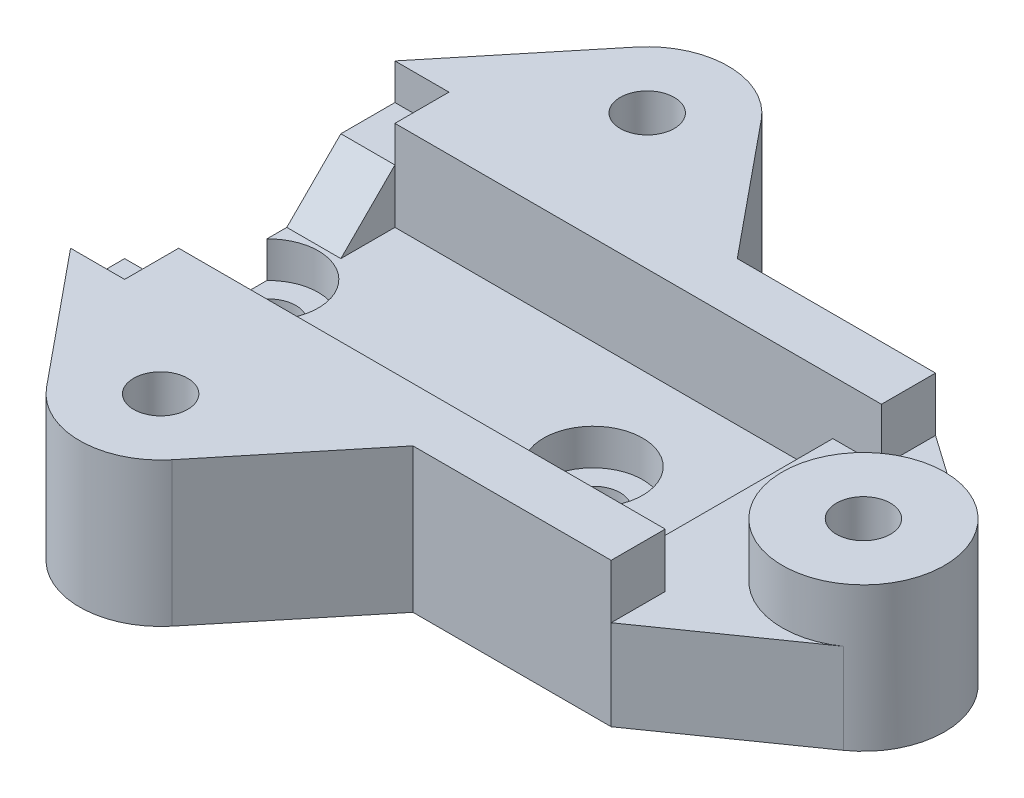
SolidWorks part; units mm, degrees
ref_plane "Front" through (0, 0, 0) normal (0, 0, 1) x (1, 0, 0)
ref_plane "Top" through (0, 0, 0) normal (0, 1, 0) x (1, 0, 0)
ref_plane "Right" through (0, 0, 0) normal (1, 0, 0) x (0, 0, -1)
sketch "Эскиз1" plane through (0, 0, 0) normal (0, 1, 0) x (1, 0, 0)
  line L0 (-9.0756, 0) -> (11.0252, 0) construction
  line L1 (0, 7.5126) -> (0, -7.9496) construction
  line L3 (15, 9) -> (-15, 9)
  line L4 (15, 9) -> (15, -9)
  line L5 (15, -9) -> (-15, -9)
  line L6 (-15, 9) -> (-15, -9)
  line L7 (15, 9) -> (-15, -9) construction
  line L8 (15, -9) -> (-15, 9) construction
  point P5 (0, 0)
  dimension "D1" = 18
  dimension "D2" = 30
extrude "Бобышка-Вытянуть1" add sketch "Эскиз1" along normal blind 3
sketch "Эскиз2" plane through (0, 3, 0) normal (0, 1, 0) x (1, 0, 0)
  line L0 (-15, 0) -> (15, 0) construction
  line L1 (-15, 9) -> (-15, -9) construction
  line L2 (15, -9) -> (15, 9) construction
  line L3 (-15, -9) -> (15, -9) construction
  line L4 (-12, -9) -> (15, -9)
  line L5 (-12, -9) -> (-12, -6)
  line L6 (-12, -6) -> (15, -6)
  line L7 (15, -9) -> (15, -6)
  line L8 (15, 9) -> (15, 6)
  line L9 (-12, 9) -> (-12, 6)
  line L10 (-12, 6) -> (15, 6)
  line L11 (-12, 9) -> (15, 9)
  dimension "D1" = 3
  dimension "D2" = 12
extrude "Бобышка-Вытянуть2" add sketch "Эскиз2" along normal blind 5
sketch "Эскиз3" plane through (0, 3, 0) normal (0, 1, 0) x (1, 0, 0)
  line L0 (15, -6) -> (-12, -6) construction
  line L1 (15, 6) -> (12.3, 6)
  line L2 (15, 6) -> (15, -6)
  line L3 (15, -6) -> (12.3, -6)
  line L4 (12.3, 6) -> (12.3, -6)
  line L8 (-12, 9) -> (-12, 6) construction
  dimension "D1" = 24.3
extrude "Бобышка-Вытянуть3" add sketch "Эскиз3" along normal blind 2
sketch "Эскиз4" plane through (0, 0, 0) normal (0, 1, 0) x (1, 0, 0)
  line L0 (15, -6) -> (15, 6) construction
  circle A0 centre (20, 0) radius 1.5
  circle A1 centre (20, 0) radius 4.5
  dimension "D1" = 3
  dimension "D3" = 9
  dimension "D2" = 5
extrude "Бобышка-Вытянуть4" add sketch "Эскиз4" along normal up to surface (8 mm away) separate body up to face at (1.5, 8, -7.5)
sketch "Эскиз5" plane through (0, 0, 0) normal (0, -1, 0) x (1, 0, 0)
  line L0 (15, 9) -> (22.5829, 3.6849)
  line L1 (15, -9) -> (22.5829, -3.6849)
  line L2 (15, 9) -> (15, -9)
  circle A0 centre (20, 0) radius 4.5 construction
  circle A2 centre (20, 0) radius 4.5
  arc A3 (22.5829, 3.6849) -> (22.5829, -3.6849) centre (20, 0) ccw
  dimension "D1" = 0
extrude "Бобышка-Вытянуть5" add sketch "Эскиз5" against normal up to surface (5 mm away) up to face at (13.65, 5, 0)
sketch "Эскиз7" plane through (-12, 0, 0) normal (-1, 0, 0) x (0, 0, 1)
  line L0 (9, 6) -> (6, 6)
  line L1 (9, 8) -> (9, 3) construction
  line L2 (6, 8) -> (6, 3) construction
  line L3 (6, 6) -> (3, 3)
  line L4 (3, 3) -> (9, 3)
  line L5 (9, 3) -> (9, 6)
  line L6 (0, 0) -> (0, 5.1893) construction
  line L7 (-3, 3) -> (-9, 3)
  line L8 (-9, 3) -> (-9, 6)
  line L9 (-9, 6) -> (-6, 6)
  line L10 (-6, 6) -> (-3, 3)
  dimension "D1" = 45
  dimension "D2" = 3
extrude "Бобышка-Вытянуть6" add sketch "Эскиз7" along normal up to surface (3 mm away) up to face at (-15, 1.5, 0)
sketch "Эскиз8" plane through (0, 0, 0) normal (0, 1, 0) x (1, 0, 0)
  line L0 (0, 0) -> (14.0942, 0) construction
  line L1 (-5.5, -13.5) -> (-5.5, 13.6667) construction
  line L2 (4, -9) -> (-2.0181, -16.3507)
  line L3 (-15, -9) -> (-8.9819, -16.3507)
  line L4 (-15, 9) -> (-8.9819, 16.3507)
  line L5 (4, 9) -> (-2.0181, 16.3507)
  line L6 (4, 9) -> (-15, 9)
  line L8 (4, -9) -> (-15, -9)
  line L10 (-15, -9) -> (15, -9) construction
  circle A0 centre (-5.5, 13.5) radius 1.5
  circle A1 centre (-5.5, -13.5) radius 1.5
  circle A2 centre (-5.5, 13.5) radius 4.5
  circle A3 centre (-5.5, -13.5) radius 4.5
  line M9 (-2.5606, -16.85) -> (-0.2025, -5.2975)
  line M13 (-0.2025, 5.2975) -> (-2.5606, 16.85)
  arc M14 (-2.5606, 16.85) -> (-8.4394, 16.85) centre (-5.5, 16.25) ccw
  line M15 (-8.4394, 16.85) -> (-10.7975, 5.2975)
  line M19 (-10.7975, -5.2975) -> (-8.4394, -16.85)
  arc M20 (-8.4394, -16.85) -> (-2.5606, -16.85) centre (-5.5, -16.25) ccw
  circle M26 centre (-5.5, -10.4167) radius 0.75
  circle M30 centre (-5.5, 10.4167) radius 0.75
  circle M32 centre (-5.5, -16.25) radius 0.75
  circle M33 centre (-5.5, 16.25) radius 0.75
  dimension "D3" = 9
  dimension "D4" = 3
  dimension "D2" = 9.5
  dimension "D5" = 13.5
sketch "Эскиз11" plane through (0, 0, 0) normal (0, -1, 0) x (1, 0, 0)
  line L0 (-15, -9) -> (-15, 9) construction
  circle A0 centre (-13, 0) radius 1.5
  point P0 (-15, 0)
  dimension "D1" = 3
  dimension "D2" = 2
extrude "Вырез-Вытянуть1" cut sketch "Эскиз11" against normal up to surface (3 mm away) up to face at (-5.1562, 3, 0)
sketch "Эскиз12" plane through (0, 3, 0) normal (0, 1, 0) x (1, 0, 0)
  circle A0 centre (-13, 0) radius 2.75
  dimension "D1" = 5.5
extrude "Вырез-Вытянуть2" cut sketch "Эскиз12" against normal blind 2
extrude "Бобышка-Вытянуть7" add sketch "Эскиз8" along normal up to surface (8 mm away) contours L5 A2 L6 M13 | A2 M14 M13 | A2 A0 M14 M15 M13 M30 M33 | A2 L6 M13 | A2 L4 L6 M15 | A2 M15 M14 | L6 A2 M15 | A3 L2 L8 M9 | A3 L8 M9 | A3 L8 M19 | A3 L8 L3 M19 | A3 A1 M20 M9 M19 M32 M26 | A3 M20 M9 | A3 M20 M19 | M26 | M32 | M33 | M30 up to face at (1.5, 8, 7.5)
sketch "Эскиз13" plane through (0, 0, 0) normal (0, -1, 0) x (1, 0, 0)
  line L0 (0, 0) -> (17.147, 0) construction
  circle A0 centre (5, 0) radius 1.5
  dimension "D1" = 10.5
  dimension "D2" = 3
extrude "Вырез-Вытянуть3" cut sketch "Эскиз13" against normal up to surface (3 mm away) up to face at (-6.65, 3, 0)
sketch "Эскиз14" plane through (0, 3, 0) normal (0, 1, 0) x (1, 0, 0)
  circle A0 centre (5, 0) radius 2.75
  circle A1 centre (5, 0) radius 1.5 construction
  dimension "D1" = 5.5
extrude "Вырез-Вытянуть4" cut sketch "Эскиз14" against normal blind 2
